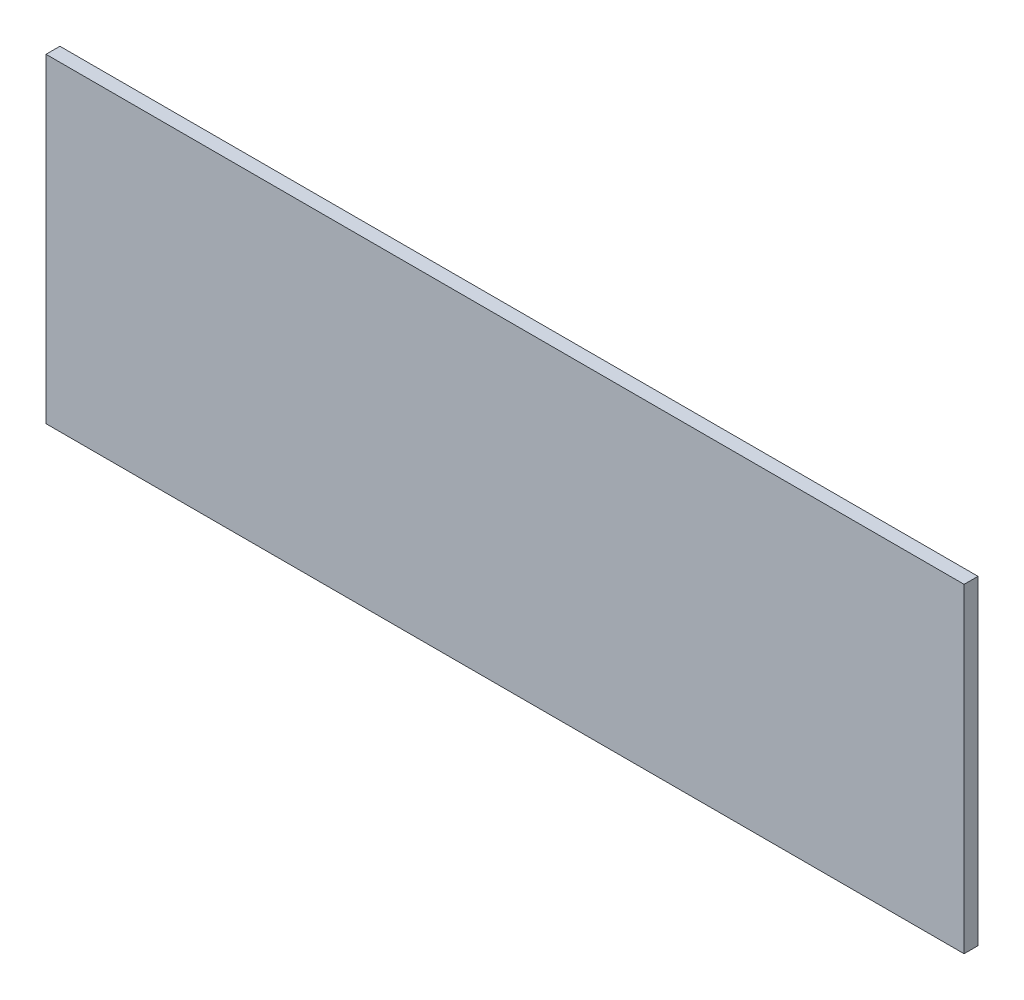
SolidWorks part; units mm, degrees
ref_plane "前视基准面" through (0, 0, 0) normal (0, 0, 1) x (1, 0, 0)
ref_plane "上视基准面" through (0, 0, 0) normal (0, 1, 0) x (1, 0, 0)
ref_plane "右视基准面" through (0, 0, 0) normal (1, 0, 0) x (0, 0, -1)
sketch "草图1" plane through (0, 0, 0) normal (0, 0, 1) x (1, 0, 0)
  line L1 (-330, 115) -> (330, 115)
  line L2 (-330, 115) -> (-330, -115)
  line L3 (-330, -115) -> (330, -115)
  line L4 (330, 115) -> (330, -115)
  line L5 (-330, 115) -> (330, -115) construction
  line L6 (-330, -115) -> (330, 115) construction
  point P0 (0, 0)
  dimension "D1" = 660
  dimension "D2" = 230
extrude "凸台-拉伸1" add sketch "草图1" along normal blind 10
